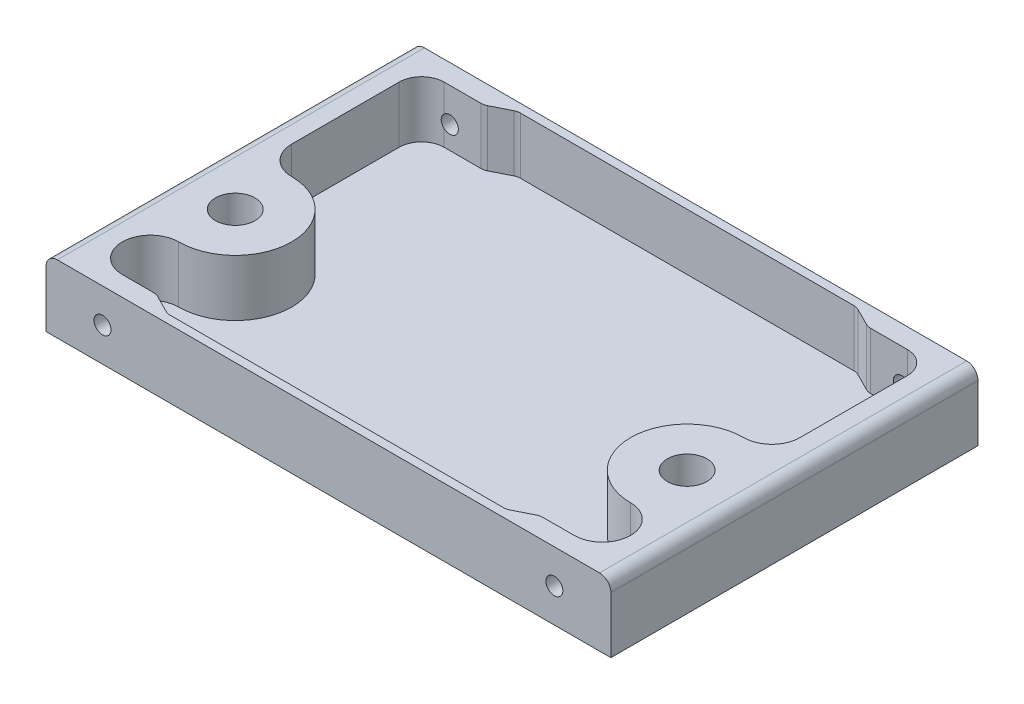
SolidWorks part; units mm, degrees
ref_plane "前视基准面" through (0, 0, 0) normal (0, 0, 1) x (1, 0, 0)
ref_plane "上视基准面" through (0, 0, 0) normal (0, 1, 0) x (1, 0, 0)
ref_plane "右视基准面" through (0, 0, 0) normal (1, 0, 0) x (0, 0, -1)
other "Configuration Table"
sketch "草图1" plane through (0, 0, 0) normal (0, 1, 0) x (1, 0, 0)
  line L1 (-50, -32.5) -> (50, -32.5)
  line L2 (-50, -32.5) -> (-50, 32.5)
  line L3 (-50, 32.5) -> (50, 32.5)
  line L4 (50, -32.5) -> (50, 32.5)
  line L5 (-50, -32.5) -> (50, 32.5) construction
  line L6 (-50, 32.5) -> (50, -32.5) construction
  point P0 (0, 0)
  dimension "D1" = 100
  dimension "D2" = 65
extrude "凸台-拉伸1" add sketch "草图1" along normal blind 12
sketch "草图2" plane through (0, 12, 0) normal (0, 1, 0) x (1, 0, 0)
  line L0 (0, -37.9045) -> (0, 37.9045) construction
  line L6 (-30.4223, 30.7889) -> (-33.5777, 29.2111)
  line L7 (-34.4721, 29) -> (-41, 29)
  line L8 (-29.5279, 31) -> (29.5279, 31)
  line L9 (-50, 32.5) -> (-50, -32.5) construction
  line L10 (-40, -52.6045) -> (-40, 4.7784) construction
  line L11 (-40, -29) -> (-34.4392, -29)
  line L12 (29.5239, -31) -> (-29.5239, -31)
  line L13 (-33.5382, -29.2145) -> (-30.425, -30.7855)
  line L14 (-50, -32.5) -> (50, -32.5) construction
  line L15 (-45, 6) -> (-45, 25)
  line L16 (-45, 49.1756) -> (-45, -43.1392) construction
  line L17 (-30, 31) -> (-30, -37.9045) construction
  line L18 (30, 31) -> (30, -37.9045) construction
  line L19 (45, 6) -> (45, 25)
  line L20 (33.5382, -29.2145) -> (30.425, -30.7855)
  line L21 (40, -29) -> (34.4392, -29)
  line L22 (34.4721, 29) -> (41, 29)
  line L23 (30.4223, 30.7889) -> (33.5777, 29.2111)
  arc A0 (-41, 29) -> (-45, 25) centre (-41, 25) ccw
  arc A1 (-29.5279, 31) -> (-30.4223, 30.7889) centre (-29.5279, 29) ccw
  arc A2 (-33.5777, 29.2111) -> (-34.4721, 29) centre (-34.4721, 31) cw
  circle A3 centre (-40, -9) radius 3.5
  arc A4 (-40, -19) -> (-40, 1) centre (-40, -9) ccw
  arc A5 (-40, -19) -> (-40, -29) centre (-40, -24) ccw
  arc A6 (-40, 1) -> (-45, 6) centre (-40, 6) cw
  arc A7 (-29.5239, -31) -> (-30.425, -30.7855) centre (-29.5239, -29) cw
  arc A8 (-34.4392, -29) -> (-33.5382, -29.2145) centre (-34.4392, -31) cw
  arc A9 (34.4392, -29) -> (33.5382, -29.2145) centre (34.4392, -31) ccw
  arc A10 (29.5239, -31) -> (30.425, -30.7855) centre (29.5239, -29) ccw
  arc A11 (40, 1) -> (45, 6) centre (40, 6) ccw
  arc A12 (40, -19) -> (40, -29) centre (40, -24) cw
  arc A13 (40, -19) -> (40, 1) centre (40, -9) cw
  circle A14 centre (40, -9) radius 3.5
  arc A15 (33.5777, 29.2111) -> (34.4721, 29) centre (34.4721, 31) ccw
  arc A16 (29.5279, 31) -> (30.4223, 30.7889) centre (29.5279, 29) cw
  arc A17 (41, 29) -> (45, 25) centre (41, 25) cw
  point P3 (0, 0)
  point P6 (30, -31)
  point P9 (-30, 31)
  point P11 (0, 31)
  point P18 (-34, 29)
  point P35 (0, 31)
  point P37 (-30, -31)
  point P69 (0, -31)
  point P70 (34, 29)
  dimension "D5" = 4
  dimension "D2" = 2
  dimension "D4" = 7
  dimension "D10" = 2
  dimension "D13" = 5
  dimension "D1" = 30
  dimension "D3" = 23.5
  dimension "D6" = 7
  dimension "D7" = 3.5
  dimension "D8" = 10
  dimension "D9" = 30
  dimension "D11" = 62
  dimension "D12" = 1.5
extrude "切除-拉伸2" cut sketch "草图2" against normal blind 10 contours A9 L20 A10 L12 A7 L13 A8 L11 A5 A4 A6 L15 A0 L7 A2 L6 A1 L8 A16 L23 A15 L22 A17 L19 A11 A13 A12 L21 | A3 | A14
sketch "草图3" plane through (0, 2, 0) normal (0, 1, 0) x (1, 0, 0)
  circle A0 centre (-40, -9) radius 3.5
extrude "切除-拉伸3" cut sketch "草图3" against normal through all contours A0
sketch "草图4" plane through (0, 2, 0) normal (0, 1, 0) x (1, 0, 0)
  circle A0 centre (40, -9) radius 3.5
extrude "切除-拉伸4" cut sketch "草图4" against normal through all
sketch "草图5" plane through (0, 0, 32.5) normal (0, 0, 1) x (1, 0, 0)
  line L0 (50, 12) -> (50, 0) construction
  line L1 (-50, 0) -> (50, 0) construction
  line L2 (-50, 12) -> (-50, 0) construction
  circle A0 centre (-40, 6) radius 1.5
  circle A1 centre (40, 6) radius 1.5
  dimension "D1" = 3
  dimension "D2" = 3
  dimension "D3" = 10
  dimension "D4" = 6
  dimension "D5" = 6
  dimension "D6" = 10
extrude "切除-拉伸5" cut sketch "草图5" against normal up to next
sketch "草图6" plane through (0, 0, -32.5) normal (0, 0, -1) x (-1, 0, 0)
  line L0 (50, 12) -> (50, 0) construction
  line L1 (-50, 0) -> (50, 0) construction
  line L2 (-50, 12) -> (-50, 0) construction
  circle A0 centre (-40, 6) radius 1.5
  circle A1 centre (40, 6) radius 1.5
  dimension "D1" = 3
  dimension "D2" = 3
  dimension "D3" = 10
  dimension "D4" = 6
  dimension "D5" = 10
  dimension "D6" = 6
extrude "切除-拉伸6" cut sketch "草图6" against normal up to next
fillet "圆角3" radius 2 2 edges at (-50, 12, 0) (50, 12, 0)
